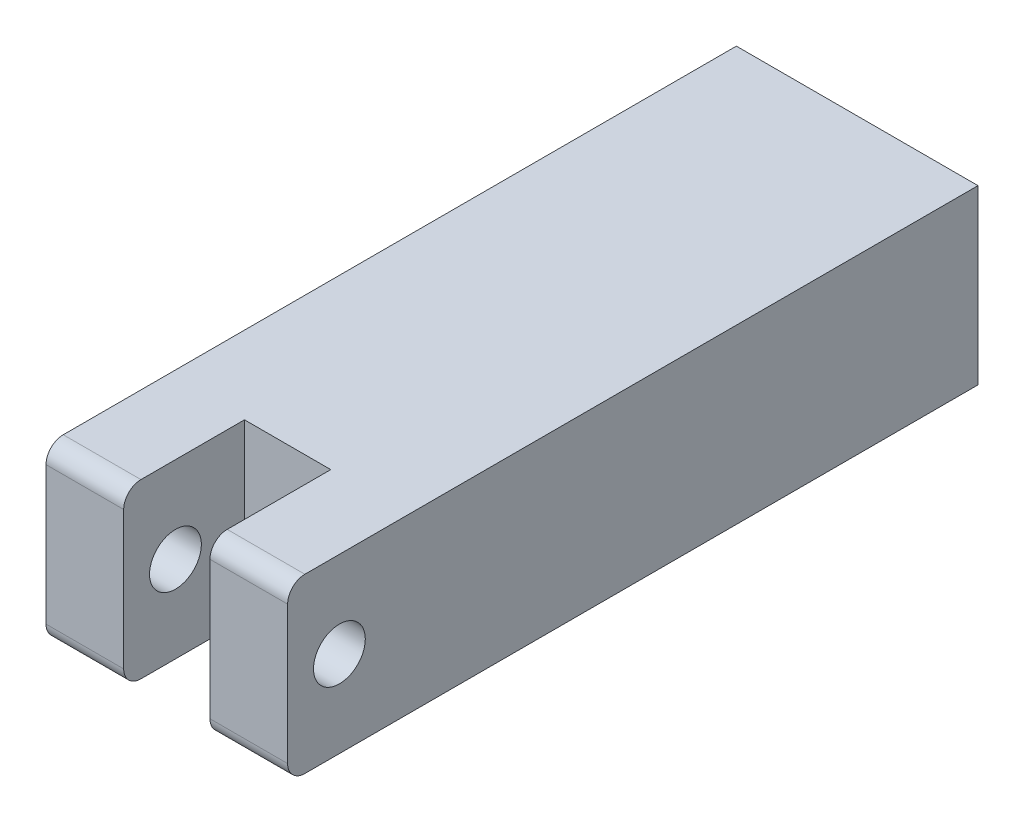
SolidWorks part; units mm, degrees
ref_plane "Alzado" through (0, 0, 0) normal (0, 0, 1) x (1, 0, 0)
ref_plane "Planta" through (0, 0, 0) normal (0, 1, 0) x (1, 0, 0)
ref_plane "Vista lateral" through (0, 0, 0) normal (1, 0, 0) x (0, 0, -1)
sketch "Croquis1" plane through (0, 0, 0) normal (1, 0, 0) x (0, 0, -1)
  line L3 (-24, 5) -> (15, 5)
  line L4 (-25, 4) -> (-25, -4)
  line L5 (-24, -5) -> (15, -5)
  line L6 (15, 5) -> (15, -5)
  arc A2 (-25, -4) -> (-24, -5) centre (-24, -4) ccw
  arc A3 (-24, 5) -> (-25, 4) centre (-24, 4) ccw
  circle A4 centre (-22, 0) radius 1.5
  point P0 (0, 0)
  point P2 (15, 0)
  dimension "D3" = 1
  dimension "D4" = 3
  dimension "D5" = 3
  dimension "D1" = 10
  dimension "D2" = 25
  dimension "D6" = 15
extrude "Saliente-Extruir1" add sketch "Croquis1" along normal mid plane 14
sketch "Croquis2" plane through (0, 0, 0) normal (0, 0, 1) x (1, 0, 0)
  circle A0 centre (0, 0) radius 1.5
  dimension "D1" = 3
extrude "Cortar-Extruir1" cut sketch "Croquis2" against normal through all and the other way blind 13
sketch "Croquis3" plane through (0, 0, 0) normal (0, 1, 0) x (1, 0, 0)
  line L0 (7, -24) -> (-7, -24) construction
  line L1 (-2.5, -18) -> (2.5, -18)
  line L2 (-2.5, -18) -> (-2.5, -25)
  line L3 (-2.5, -25) -> (2.5, -25)
  line L4 (2.5, -18) -> (2.5, -25)
  line L5 (7, -25) -> (-7, -25) construction
  point P6 (0, -24)
  point P7 (0, -25)
  point P8 (0, -18)
  dimension "D1" = 7
  dimension "D2" = 5
extrude "Cortar-Extruir2" cut sketch "Croquis3" against normal through all both and the other way through all
sketch "Croquis4" plane through (0, 0, 0) normal (0, 0, 1) x (1, 0, 0)
  line L1 (1.7321, 3) -> (-1.7321, 3)
  line L2 (-1.7321, 3) -> (-3.4641, 0)
  line L3 (-3.4641, 0) -> (-1.7321, -3)
  line L4 (-1.7321, -3) -> (1.7321, -3)
  line L5 (1.7321, -3) -> (3.4641, 0)
  line L6 (3.4641, 0) -> (1.7321, 3)
  circle A0 centre (0, 0) radius 3 construction
  dimension "D1" = 6
extrude "Cortar-Extruir3" cut sketch "Croquis4" against normal mid plane 3
sketch "Croquis5" plane through (0, 0, 0) normal (1, 0, 0) x (0, 0, -1)
  line L1 (-1.5, 3) -> (1.5, 3)
  line L2 (-1.5, 3) -> (-1.5, -3)
  line L3 (-1.5, -3) -> (1.5, -3)
  line L4 (1.5, 3) -> (1.5, -3)
extrude "Cortar-Extruir4" cut sketch "Croquis5" against normal through all
